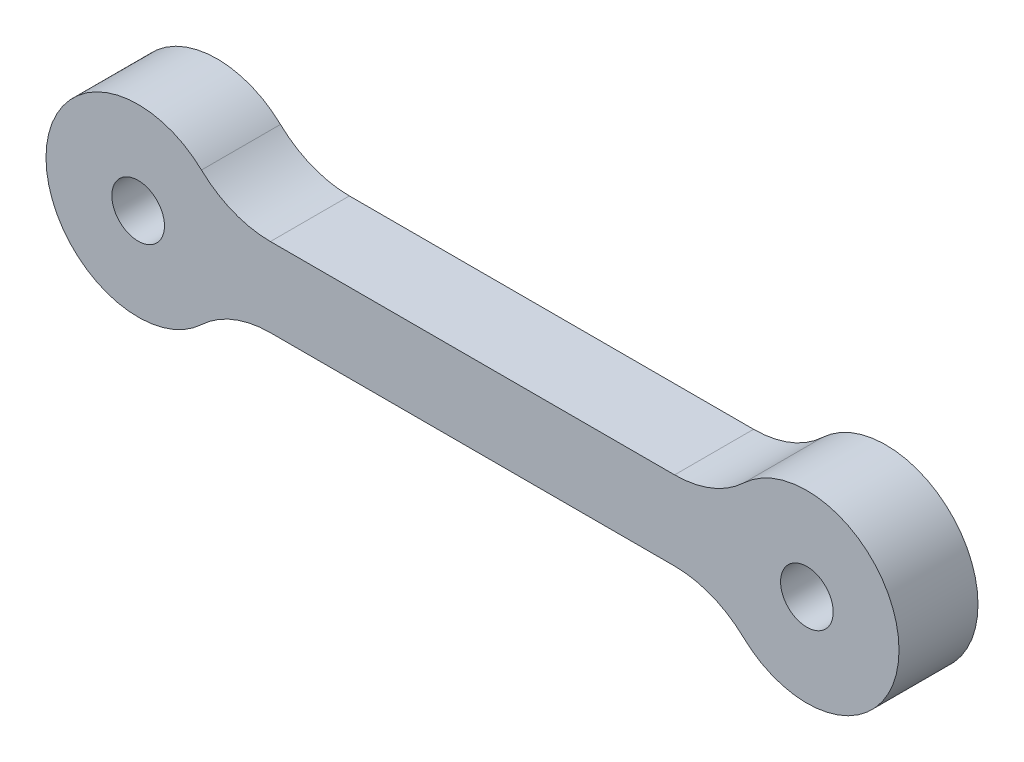
SolidWorks part; units mm, degrees
material "Plain Carbon Steel"
ref_plane "Front Plane" through (0, 0, 0) normal (0, 0, 1) x (1, 0, 0)
ref_plane "Top Plane" through (0, 0, 0) normal (0, 1, 0) x (1, 0, 0)
ref_plane "Right Plane" through (0, 0, 0) normal (1, 0, 0) x (0, 0, -1)
sketch "스케치1" plane through (0, 0, 0) normal (0, 0, 1) x (1, 0, 0)
  line L0 (12.7, 0) -> (-12.7, 0) construction
  line L1 (-9.5377, -1.5) -> (9.5377, -1.5)
  line L2 (-9.5377, -1.5) -> (-9.5377, 1.5) construction
  line L3 (-9.5377, 1.5) -> (9.5377, 1.5)
  line L4 (9.5377, -1.5) -> (9.5377, 1.5) construction
  line L5 (-9.5377, -1.5) -> (9.5377, 1.5) construction
  line L6 (-9.5377, 1.5) -> (9.5377, -1.5) construction
  circle A0 centre (-12.7, 0) radius 3.5 construction
  circle A1 centre (12.7, 0) radius 3.5 construction
  circle A2 centre (-12.7, 0) radius 1
  circle A3 centre (12.7, 0) radius 1
  arc A4 (-9.5377, 1.5) -> (-9.5377, -1.5) centre (-12.7, 0) ccw
  arc A5 (9.5377, 1.5) -> (9.5377, -1.5) centre (12.7, 0) cw
  point P0 (0, 0)
  dimension "D2" = 2.5
  dimension "D3" = 2
  dimension "D4" = 25.4
  dimension "D1" = 3
extrude "보스-돌출1" add sketch "스케치1" along normal blind 3
fillet "필렛1" radius 3.81 4 edges at (-9.5377, -1.5, 1.5) (9.5377, -1.5, 1.5) (9.5377, 1.5, 1.5) (-9.5377, 1.5, 1.5)
sketch "스케치2" plane through (0, 0, 3) normal (0, 0, 1) x (1, 0, 0)
  line L0 (-4.572, 0) -> (4.572, 0) construction
  circle A0 centre (-4.572, 0) radius 0.25
  circle A1 centre (4.572, 0) radius 0.25
  dimension "D1" = 0.5
  dimension "D2" = 0.5
  dimension "D3" = 4.572
extrude "컷-돌출1" [suppressed] cut sketch "스케치2" against normal up to surface (3 mm away)
